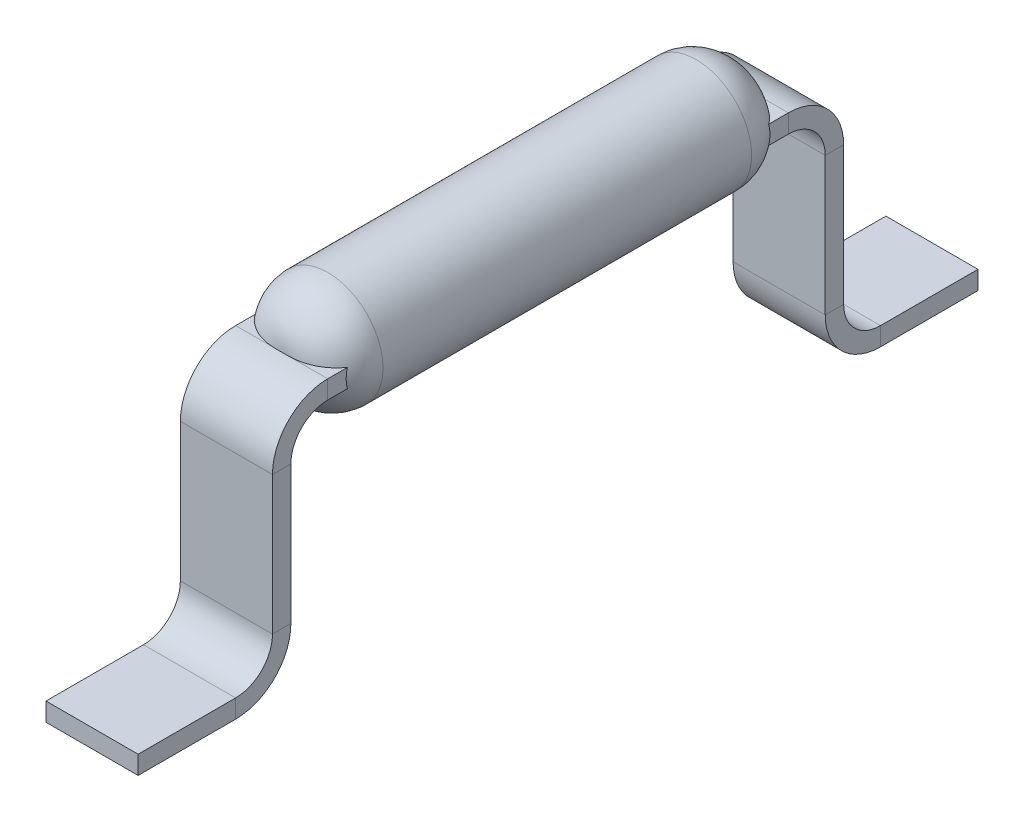
SolidWorks part; units mm, degrees
ref_plane "Front Plane" through (0, 0, 0) normal (0, 0, 1) x (1, 0, 0)
ref_plane "Top Plane" through (0, 0, 0) normal (0, 1, 0) x (1, 0, 0)
ref_plane "Right Plane" through (0, 0, 0) normal (1, 0, 0) x (0, 0, -1)
sketch "Sketch1" plane through (0, 0, 0) normal (1, 0, 0) x (0, 0, -1)
  line L0 (0, 0) -> (0, 22.907) construction
  line L1 (-45.5814, 0) -> (-35, 0)
  line L2 (-30, 5) -> (-30, 20)
  line L3 (-25, 25) -> (25, 25)
  line L4 (30, 20) -> (30, 5)
  line L5 (35, 0) -> (45.5814, 0)
  arc A0 (30, 5) -> (35, 0) centre (35, 5) ccw
  arc A1 (25, 25) -> (30, 20) centre (25, 20) cw
  arc A2 (-30, 20) -> (-25, 25) centre (-25, 20) cw
  arc A3 (-35, 0) -> (-30, 5) centre (-35, 5) ccw
  point P8 (45.5814, 0)
  point P14 (30, 25)
  point P17 (-30, 25)
  dimension "D3" = 5
  dimension "D1" = 60
  dimension "D2" = 25
ref_plane "Plane1" through (0, 0, 45.5814) normal (0, 0, 1) x (1, 0, 0)
sketch "Sketch2" plane through (0, 0, 45.5814) normal (0, 0, 1) x (1, 0, 0)
  line L1 (-5, -1) -> (5, -1)
  line L2 (-5, -1) -> (-5, 1)
  line L3 (-5, 1) -> (5, 1)
  line L4 (5, -1) -> (5, 1)
  line L5 (-5, -1) -> (5, 1) construction
  line L6 (-5, 1) -> (5, -1) construction
  point P0 (0, 0)
  dimension "D1" = 2
  dimension "D2" = 10
sweep "Sweep1" add profiles "Sketch2" path "Sketch1"
sketch "Sketch3" plane through (0, 0, 0) normal (1, 0, 0) x (0, 0, -1)
  line L0 (-25, 25) -> (25, 25) construction
  line L1 (-25, 24) -> (-25, 26) construction
  line L2 (25, 24) -> (25, 26) construction
  line L3 (-25, 25) -> (-25, 26)
  line L4 (-20, 31) -> (20, 31)
  line L5 (25, 26) -> (25, 25)
  line L6 (25, 25) -> (-25, 25)
  line L7 (0, 24) -> (0, 43.1351) construction
  line L8 (-25, 24) -> (25, 24) construction
  line L9 (-25, 26) -> (25, 26) construction
  arc A0 (20, 31) -> (25, 26) centre (20, 26) cw
  arc A1 (-25, 26) -> (-20, 31) centre (-20, 26) cw
  dimension "D3" = 5
  dimension "D1" = 5
  dimension "D2" = 50
revolve "Revolve1" add sketch "Sketch3" angle 360 about L6
